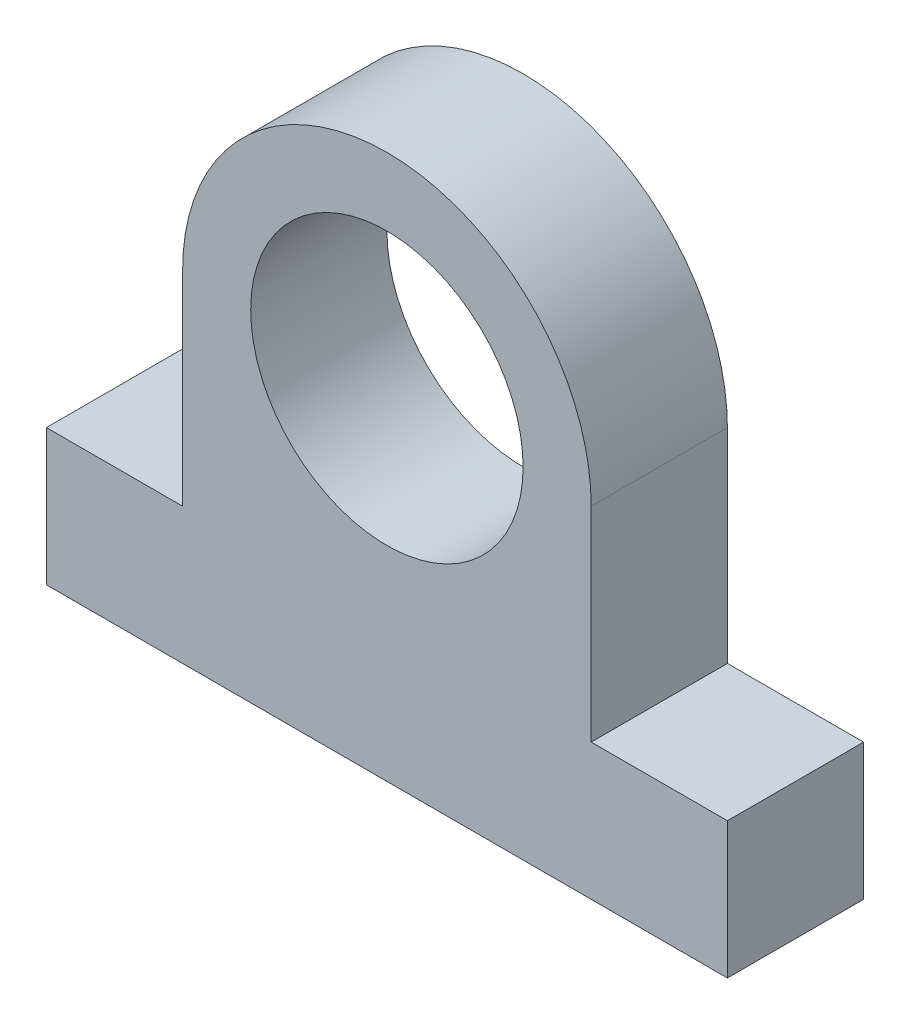
SolidWorks part; units mm, degrees
ref_plane "Front Plane" through (0, 0, 0) normal (0, 0, 1) x (1, 0, 0)
ref_plane "Top Plane" through (0, 0, 0) normal (0, 1, 0) x (1, 0, 0)
ref_plane "Right Plane" through (0, 0, 0) normal (1, 0, 0) x (0, 0, -1)
sketch "Sketch1" plane through (0, 0, 0) normal (0, 0, 1) x (1, 0, 0)
  line L0 (-14.8897, 4.9352) -> (-14.8897, 19.9352)
  line L1 (25.1103, 4.9352) -> (-24.8897, 4.9352)
  line L2 (25.1103, 4.9352) -> (25.1103, -5.0648)
  line L3 (25.1103, -5.0648) -> (-24.8897, -5.0648)
  line L4 (-24.8897, 4.9352) -> (-24.8897, -5.0648)
  line L5 (15.1103, 4.9352) -> (15.1103, 19.9352)
  arc A0 (-14.8897, 19.9352) -> (15.1103, 19.9352) centre (0.1103, 19.9352) cw
  circle A1 centre (0.1103, 19.9352) radius 10
  dimension "D3" = 20
  dimension "D1" = 50
  dimension "D2" = 10
  dimension "D5" = 15
extrude "Extrude1" add sketch "Sketch1" along normal blind 10 contours A0 L0 L1 L5 A1 | L1 L4 L3 L2
